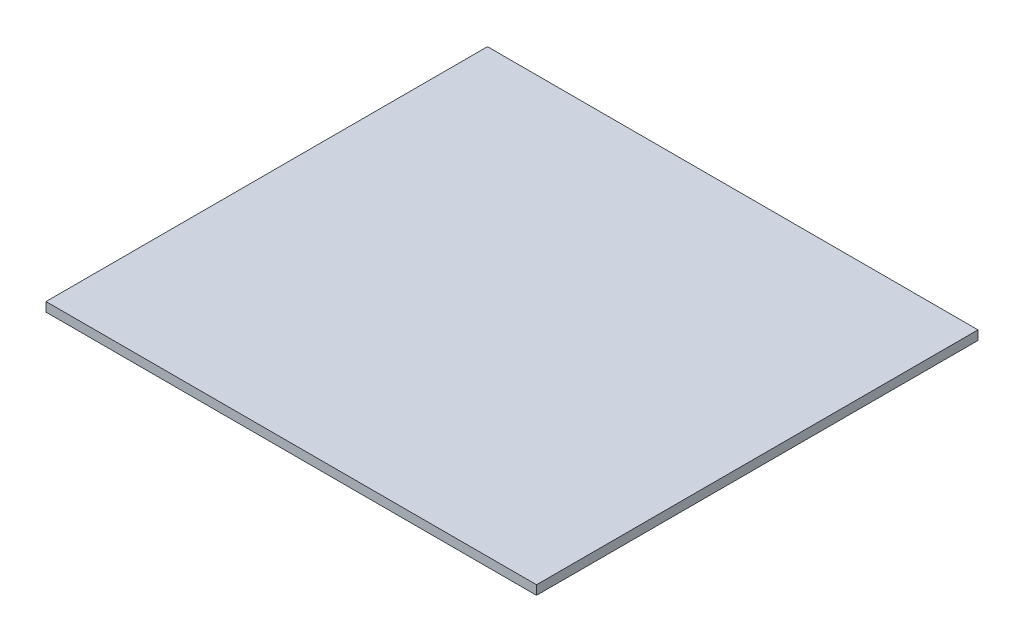
SolidWorks part; units mm, degrees
material "Oak"
ref_plane "Front" through (0, 0, 0) normal (0, 0, 1) x (1, 0, 0)
ref_plane "Top" through (0, 0, 0) normal (0, 1, 0) x (1, 0, 0)
ref_plane "Right" through (0, 0, 0) normal (1, 0, 0) x (0, 0, -1)
sketch "Sketch1" plane through (0, 0, 0) normal (0, 1, 0) x (1, 0, 0)
  line L1 (0, 0) -> (1016, 0)
  line L2 (0, 0) -> (0, 914.4)
  line L3 (0, 914.4) -> (1016, 914.4)
  line L4 (1016, 0) -> (1016, 914.4)
  dimension "D1" = 1016
  dimension "D2" = 914.4
extrude "Boss-Extrude1" add sketch "Sketch1" along normal blind 19.05
equation "\"JOE\"= 1in"
equation "\"D2@Sketch1\"=\"DEPTH@shapeoko_enclosure.sldasm\""
equation "\"D1@Sketch1\"=\"WIDTH@shapeoko_enclosure.sldasm\""
equation "\"D1@Boss-Extrude1\"=\"MAT_THICKNESS@shapeoko_enclosure.sldasm\""
